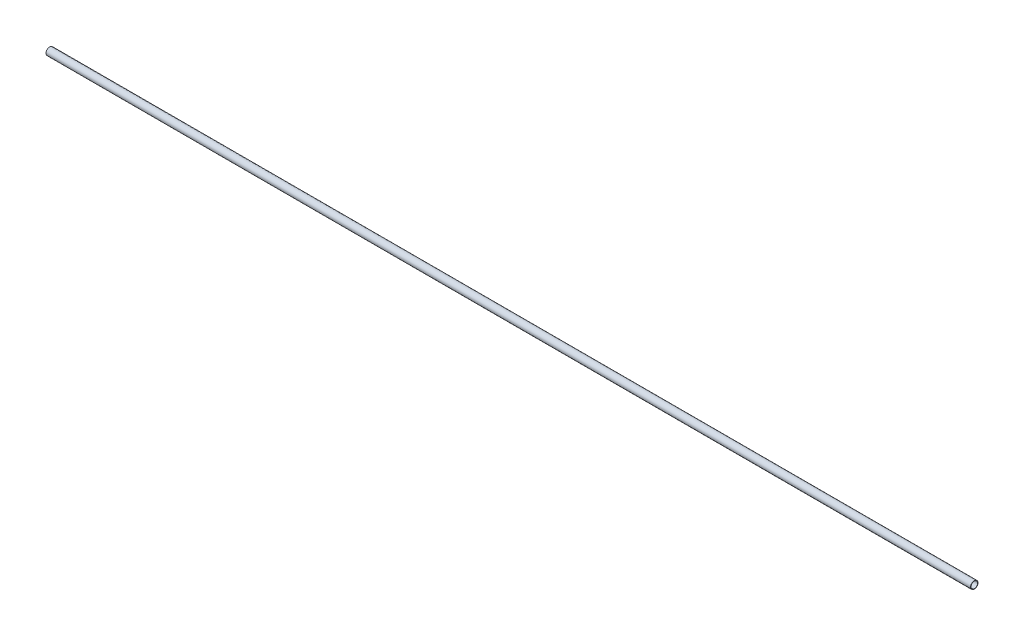
SolidWorks part; units mm, degrees
material "Galvanized Steel"
ref_plane "Front Plane" through (0, 0, 0) normal (0, 0, 1) x (1, 0, 0)
ref_plane "Top Plane" through (0, 0, 0) normal (0, 1, 0) x (1, 0, 0)
ref_plane "Right Plane" through (0, 0, 0) normal (1, 0, 0) x (0, 0, -1)
sketch "Sketch1" plane through (0, 0, 0) normal (1, 0, 0) x (0, 0, -1)
  circle A0 centre (0, 0) radius 7.8994
  circle A1 centre (0, 0) radius 8.9662
  dimension "D1" = 15.7988
  dimension "D2" = 17.9324
extrude "Boss-Extrude1" add sketch "Sketch1" along normal blind 2235.2
